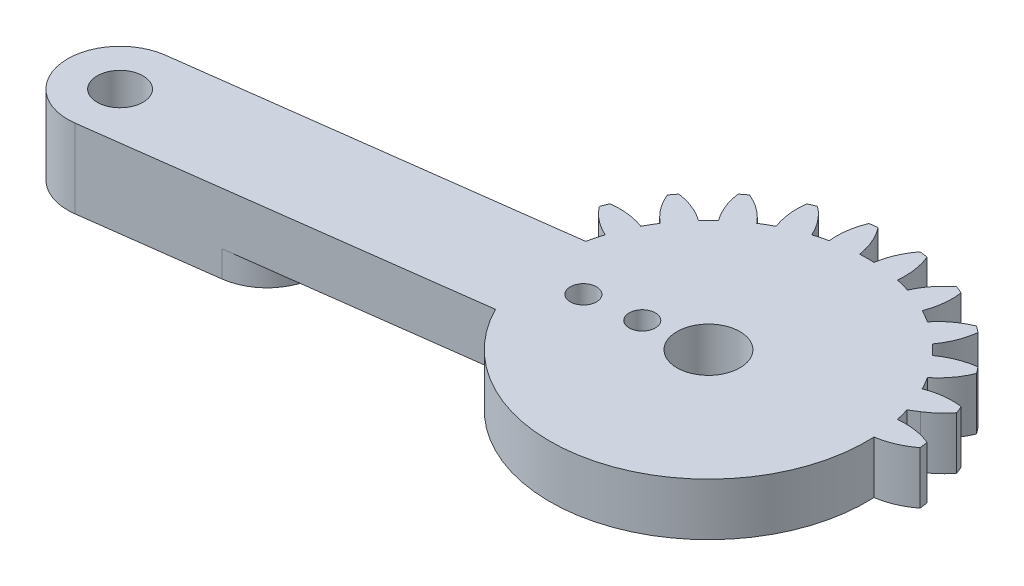
SolidWorks part; units mm, degrees
ref_plane "Front Plane" through (0, 0, 0) normal (0, 0, 1) x (1, 0, 0)
ref_plane "Top Plane" through (0, 0, 0) normal (0, 1, 0) x (1, 0, 0)
ref_plane "Right Plane" through (0, 0, 0) normal (1, 0, 0) x (0, 0, -1)
sketch "Sketch1" plane through (0, 0, 0) normal (0, 1, 0) x (1, 0, 0)
  line L0 (20, 4) -> (2.0816, 4)
  line L1 (2.0816, -4) -> (20, -4)
  arc A0 (2.0816, 4) -> (3.5217, 5.3071) centre (-0.7683, 8.5867) ccw
  arc A1 (3.5217, 5.3071) -> (3.2829, 5.8838) centre (-10.1063, 0) ccw
  arc A2 (3.2829, 5.8838) -> (0.6271, 5.5703) centre (2.5684, 0.5313) ccw
  arc A3 (0.6271, 5.5703) -> (0.0844, 6.5103) centre (-10.1063, 0) ccw
  arc A4 (0.0844, 6.5103) -> (1.6838, 8.6535) centre (-3.3089, 10.711) ccw
  arc A5 (1.6838, 8.6535) -> (1.3038, 9.1487) centre (-10.1063, 0) ccw
  arc A6 (1.3038, 9.1487) -> (-1.1803, 8.1585) centre (1.999, 3.7936) ccw
  arc A7 (-1.1803, 8.1585) -> (-1.9479, 8.926) centre (-10.1063, 0) ccw
  arc A8 (-1.9479, 8.926) -> (-0.9576, 11.4102) centre (-6.3127, 12.1053) ccw
  arc A9 (-0.9576, 11.4102) -> (-1.4528, 11.7901) centre (-10.1063, 0) ccw
  arc A10 (-1.4528, 11.7901) -> (-3.596, 10.1907) centre (0.6046, 6.7975) ccw
  arc A11 (-3.596, 10.1907) -> (-4.5361, 10.7334) centre (-10.1063, 0) ccw
  arc A12 (-4.5361, 10.7334) -> (-4.2225, 13.3892) centre (-9.5751, 12.6747) ccw
  arc A13 (-4.2225, 13.3892) -> (-4.7992, 13.6281) centre (-10.1063, 0) ccw
  arc A14 (-4.7992, 13.6281) -> (-6.4554, 11.5285) centre (-1.5196, 9.3381) ccw
  arc A15 (-6.4554, 11.5285) -> (-7.5039, 11.8094) centre (-10.1063, 0) ccw
  arc A16 (-7.5039, 11.8094) -> (-7.8884, 14.4558) centre (-12.8736, 12.3803) ccw
  arc A17 (-7.8884, 14.4558) -> (-8.5072, 14.5373) centre (-10.1063, 0) ccw
  arc A18 (-8.5072, 14.5373) -> (-9.5636, 12.0806) centre (-4.2291, 11.2423) ccw
  arc A19 (-9.5636, 12.0806) -> (-10.6491, 12.0806) centre (-10.1063, 0) ccw
  arc A20 (-10.6491, 12.0806) -> (-11.7054, 14.5373) centre (-15.9836, 11.2423) ccw
  arc A21 (-11.7054, 14.5373) -> (-12.3243, 14.4558) centre (-10.1063, 0) ccw
  arc A22 (-12.3243, 14.4558) -> (-12.7088, 11.8094) centre (-7.3391, 12.3803) ccw
  arc A23 (-12.7088, 11.8094) -> (-13.7573, 11.5285) centre (-10.1063, 0) ccw
  arc A24 (-13.7573, 11.5285) -> (-15.4135, 13.6281) centre (-18.6931, 9.3381) ccw
  arc A25 (-15.4135, 13.6281) -> (-15.9901, 13.3892) centre (-10.1063, 0) ccw
  arc A26 (-15.9901, 13.3892) -> (-15.6766, 10.7334) centre (-10.6376, 12.6747) ccw
  arc A27 (-15.6766, 10.7334) -> (-16.6166, 10.1907) centre (-10.1063, 0) ccw
  arc A28 (-16.6166, 10.1907) -> (-18.7599, 11.7901) centre (-20.8173, 6.7975) ccw
  arc A29 (-18.7599, 11.7901) -> (-19.255, 11.4102) centre (-10.1063, 0) ccw
  arc A30 (-19.255, 11.4102) -> (-18.2648, 8.926) centre (-13.9, 12.1053) ccw
  arc A31 (-18.2648, 8.926) -> (-19.0324, 8.1585) centre (-10.1063, 0) ccw
  arc A32 (-19.0324, 8.1585) -> (-21.5165, 9.1487) centre (-22.2117, 3.7936) ccw
  arc A33 (-21.5165, 9.1487) -> (-21.8965, 8.6535) centre (-10.1063, 0) ccw
  arc A34 (-21.8965, 8.6535) -> (-20.2971, 6.5103) centre (-16.9038, 10.711) ccw
  arc A35 (-20.2971, 6.5103) -> (-20.8398, 5.5703) centre (-10.1063, 0) ccw
  arc A36 (-20.8398, 5.5703) -> (-23.4956, 5.8838) centre (-22.7811, 0.5313) ccw
  arc A37 (-23.4956, 5.8838) -> (-23.7344, 5.3071) centre (-10.1063, 0) ccw
  arc A38 (-23.7344, 5.3071) -> (-21.6348, 3.6509) centre (-19.4444, 8.5867) ccw
  arc A39 (-21.6348, 3.6509) -> (-21.9157, 2.6025) centre (-10.1063, 0) ccw
  arc A40 (-21.9157, 2.6025) -> (-24.5622, 2.2179) centre (-22.4867, -2.7673) ccw
  arc A41 (-24.5622, 2.2179) -> (-24.6437, 1.5991) centre (-10.1063, 0) ccw
  arc A42 (-24.6437, 1.5991) -> (-22.1869, 0.5427) centre (-21.3486, 5.8773) ccw
  arc A43 (-22.1869, 0.5427) -> (-22.1869, -0.5427) centre (-10.1063, 0) ccw
  arc A44 (-22.1869, -0.5427) -> (-24.6437, -1.5991) centre (-21.3486, -5.8773) ccw
  arc A45 (-24.6437, -1.5991) -> (-24.5622, -2.2179) centre (-10.1063, 0) ccw
  arc A46 (-24.5622, -2.2179) -> (-21.9157, -2.6025) centre (-22.4867, 2.7673) ccw
  arc A47 (-21.9157, -2.6025) -> (-21.6348, -3.6509) centre (-10.1063, 0) ccw
  arc A48 (-21.6348, -3.6509) -> (-23.7344, -5.3071) centre (-19.4444, -8.5867) ccw
  arc A49 (-23.7344, -5.3071) -> (-23.4956, -5.8838) centre (-10.1063, 0) ccw
  arc A50 (-23.4956, -5.8838) -> (-20.8398, -5.5703) centre (-22.7811, -0.5313) ccw
  arc A51 (-20.8398, -5.5703) -> (-20.2971, -6.5103) centre (-10.1063, 0) ccw
  arc A52 (-20.2971, -6.5103) -> (-21.8965, -8.6535) centre (-16.9038, -10.711) ccw
  arc A53 (-21.8965, -8.6535) -> (-21.5165, -9.1487) centre (-10.1063, 0) ccw
  arc A54 (-21.5165, -9.1487) -> (-19.0324, -8.1585) centre (-22.2117, -3.7936) ccw
  arc A55 (-19.0324, -8.1585) -> (-18.2648, -8.926) centre (-10.1063, 0) ccw
  arc A56 (-18.2648, -8.926) -> (-19.255, -11.4102) centre (-13.9, -12.1053) ccw
  arc A57 (-19.255, -11.4102) -> (-18.7599, -11.7901) centre (-10.1063, 0) ccw
  arc A58 (-18.7599, -11.7901) -> (-16.6166, -10.1907) centre (-20.8173, -6.7975) ccw
  arc A59 (-16.6166, -10.1907) -> (-15.6766, -10.7334) centre (-10.1063, 0) ccw
  arc A60 (-15.6766, -10.7334) -> (-15.9901, -13.3892) centre (-10.6376, -12.6747) ccw
  arc A61 (-15.9901, -13.3892) -> (-15.4135, -13.6281) centre (-10.1063, 0) ccw
  arc A62 (-15.4135, -13.6281) -> (-13.7573, -11.5285) centre (-18.6931, -9.3381) ccw
  arc A63 (-13.7573, -11.5285) -> (-12.7088, -11.8094) centre (-10.1063, 0) ccw
  arc A64 (-12.7088, -11.8094) -> (-12.3243, -14.4558) centre (-7.3391, -12.3803) ccw
  arc A65 (-12.3243, -14.4558) -> (-11.7054, -14.5373) centre (-10.1063, 0) ccw
  arc A66 (-11.7054, -14.5373) -> (-10.6491, -12.0806) centre (-15.9836, -11.2423) ccw
  arc A67 (-10.6491, -12.0806) -> (-9.5636, -12.0806) centre (-10.1063, 0) ccw
  arc A68 (-9.5636, -12.0806) -> (-8.5072, -14.5373) centre (-4.2291, -11.2423) ccw
  arc A69 (-8.5072, -14.5373) -> (-7.8884, -14.4558) centre (-10.1063, 0) ccw
  arc A70 (-7.8884, -14.4558) -> (-7.5039, -11.8094) centre (-12.8736, -12.3803) ccw
  arc A71 (-7.5039, -11.8094) -> (-6.4554, -11.5285) centre (-10.1063, 0) ccw
  arc A72 (-6.4554, -11.5285) -> (-4.7992, -13.6281) centre (-1.5196, -9.3381) ccw
  arc A73 (-4.7992, -13.6281) -> (-4.2225, -13.3892) centre (-10.1063, 0) ccw
  arc A74 (-4.2225, -13.3892) -> (-4.5361, -10.7334) centre (-9.5751, -12.6747) ccw
  arc A75 (-4.5361, -10.7334) -> (-3.596, -10.1907) centre (-10.1063, 0) ccw
  arc A76 (-3.596, -10.1907) -> (-1.4528, -11.7901) centre (0.6046, -6.7975) ccw
  arc A77 (-1.4528, -11.7901) -> (-0.9576, -11.4102) centre (-10.1063, 0) ccw
  arc A78 (-0.9576, -11.4102) -> (-1.9479, -8.926) centre (-6.3127, -12.1053) ccw
  arc A79 (-1.9479, -8.926) -> (-1.1803, -8.1585) centre (-10.1063, 0) ccw
  arc A80 (-1.1803, -8.1585) -> (1.3038, -9.1487) centre (1.999, -3.7936) ccw
  arc A81 (1.3038, -9.1487) -> (1.6838, -8.6535) centre (-10.1063, 0) ccw
  arc A82 (1.6838, -8.6535) -> (0.0844, -6.5103) centre (-3.3089, -10.711) ccw
  arc A83 (0.0844, -6.5103) -> (0.6271, -5.5703) centre (-10.1063, 0) ccw
  arc A84 (0.6271, -5.5703) -> (3.2829, -5.8838) centre (2.5684, -0.5313) ccw
  arc A85 (3.2829, -5.8838) -> (3.5217, -5.3071) centre (-10.1063, 0) ccw
  arc A86 (3.5217, -5.3071) -> (2.0816, -4) centre (-0.7683, -8.5867) ccw
  arc A87 (20, -4) -> (20, 4) centre (20, 0) ccw
  circle A88 centre (-10.1063, 0) radius 1.5
  circle A89 centre (20, 0) radius 1.5
  dimension "D1" = 3
  dimension "D2" = 3
  dimension "D4" = 4
  dimension "D3" = 20
extrude "Boss-Extrude1" add sketch "Sketch1" along normal blind 4
sketch "Sketch3" plane through (0, 4, 0) normal (0, 1, 0) x (1, 0, 0)
  line L0 (-10.1063, 0) -> (-40.8563, 0) construction
  line L1 (-10.1063, 0) -> (-49.7641, -5.221)
  line L2 (-10.6284, 3.9658) -> (-50.2862, -1.2553)
  line L3 (-9.5842, -3.9658) -> (-49.242, -9.1868)
  line L4 (-10.1063, 0) -> (-4.5096, 13.5117) construction
  line L5 (-10.1063, 0) -> (-8.1974, 14.4999) construction
  circle A0 centre (-10.1063, 0) radius 1.5
  circle A1 centre (20, 0) radius 1.5 construction
  circle A2 centre (20, 0) radius 1.5
  circle A3 centre (-49.7641, -5.221) radius 1.75
  circle A4 centre (-49.7641, -5.221) radius 4
  circle A5 centre (-10.1063, 0) radius 4
  arc A6 (-4.2225, 13.3892) -> (-4.7992, 13.6281) centre (-10.1063, 0) ccw construction
  arc A7 (-7.8884, 14.4558) -> (-8.5072, 14.5373) centre (-10.1063, 0) ccw construction
  dimension "D2" = 3
  dimension "D5" = 3.5
  dimension "D6" = 8
  dimension "D7" = 8
  dimension "D1" = 40
  dimension "D4" = 7.5
extrude "Boss-Extrude2" add sketch "Sketch3" against normal blind 4
sketch "Sketch4" plane through (0, 4, 0) normal (0, 1, 0) x (1, 0, 0)
  line L0 (20, 4) -> (2.0816, 4) construction
  line L1 (2.0816, -4) -> (20, -4) construction
  line L2 (20, 4) -> (2.0816, 4)
  line L3 (2.0816, -4) -> (20, -4)
  line L4 (2.0816, 4) -> (1.4381, 3.6001)
  line L5 (-21.6245, -5.5509) -> (-20.8986, -5.4553)
  line L6 (-10.1063, 0) -> (0.0844, 6.5103) construction
  line L7 (-10.1063, 0) -> (1.9742, 0.5427) construction
  line L8 (-24.5755, 2.1296) -> (-50.2862, -1.2553)
  line L9 (-49.242, -9.1868) -> (-23.5312, -5.8019)
  line L10 (2.0816, -4) -> (20, -4)
  line L11 (20, 4) -> (2.0816, 4)
  line L12 (-21.9429, 2.4762) -> (-50.2862, -1.2553)
  line L13 (-49.242, -9.1868) -> (-21.6245, -5.5509)
  line L14 (2.0816, -4) -> (20, -4)
  line L15 (20, 4) -> (2.0816, 4)
  circle A0 centre (-10.1063, 0) radius 12.0927
  arc A1 (3.2829, 5.8838) -> (0.6271, 5.5703) centre (2.5684, 0.5313) ccw construction
  arc A2 (3.5217, 5.3071) -> (3.2829, 5.8838) centre (-10.1063, 0) ccw construction
  arc A3 (2.0816, 4) -> (3.5217, 5.3071) centre (-0.7683, 8.5867) ccw construction
  arc A4 (20, -4) -> (20, 4) centre (20, 0) ccw construction
  arc A5 (3.5217, -5.3071) -> (2.0816, -4) centre (-0.7683, -8.5867) ccw construction
  arc A6 (3.2829, -5.8838) -> (3.5217, -5.3071) centre (-10.1063, 0) ccw construction
  arc A7 (0.6271, -5.5703) -> (3.2829, -5.8838) centre (2.5684, -0.5313) ccw construction
  arc A8 (3.2829, 5.8838) -> (0.6271, 5.5703) centre (2.5684, 0.5313) ccw
  arc A9 (3.5217, 5.3071) -> (3.2829, 5.8838) centre (-10.1063, 0) ccw
  arc A10 (2.0816, 4) -> (3.5217, 5.3071) centre (-0.7683, 8.5867) ccw
  arc A11 (20, -4) -> (20, 4) centre (20, 0) ccw
  arc A12 (3.5217, -5.3071) -> (2.0816, -4) centre (-0.7683, -8.5867) ccw
  arc A13 (3.2829, -5.8838) -> (3.5217, -5.3071) centre (-10.1063, 0) ccw
  arc A14 (0.6271, -5.5703) -> (3.2829, -5.8838) centre (2.5684, -0.5313) ccw
  arc A15 (1.9742, 0.5427) -> (4.431, 1.5991) centre (1.1359, 5.8773) ccw
  arc A16 (4.3495, 2.2179) -> (1.7031, 2.6025) centre (2.274, -2.7673) ccw
  arc A17 (4.431, 1.5991) -> (4.3495, 2.2179) centre (-10.1063, 0) ccw
  arc A95 (-21.6348, 3.6509) -> (-21.9157, 2.6025) centre (-10.1063, 0) ccw
  arc A96 (-50.2862, -1.2553) -> (-49.242, -9.1868) centre (-49.7641, -5.221) ccw
  arc A97 (-20.2971, -6.5103) -> (-21.8965, -8.6535) centre (-16.9038, -10.711) ccw
  arc A98 (-21.8965, -8.6535) -> (-21.5165, -9.1487) centre (-10.1063, 0) ccw
  arc A99 (-21.5165, -9.1487) -> (-19.0324, -8.1585) centre (-22.2117, -3.7936) ccw
  arc A100 (-19.0324, -8.1585) -> (-18.2648, -8.926) centre (-10.1063, 0) ccw
  arc A101 (-18.2648, -8.926) -> (-19.255, -11.4102) centre (-13.9, -12.1053) ccw
  arc A102 (-19.255, -11.4102) -> (-18.7599, -11.7901) centre (-10.1063, 0) ccw
  arc A103 (-18.7599, -11.7901) -> (-16.6166, -10.1907) centre (-20.8173, -6.7975) ccw
  arc A104 (-16.6166, -10.1907) -> (-15.6766, -10.7334) centre (-10.1063, 0) ccw
  arc A105 (-15.6766, -10.7334) -> (-15.9901, -13.3892) centre (-10.6376, -12.6747) ccw
  arc A106 (-15.9901, -13.3892) -> (-15.4135, -13.6281) centre (-10.1063, 0) ccw
  arc A107 (-15.4135, -13.6281) -> (-13.7573, -11.5285) centre (-18.6931, -9.3381) ccw
  arc A108 (-13.7573, -11.5285) -> (-12.7088, -11.8094) centre (-10.1063, 0) ccw
  arc A109 (-12.7088, -11.8094) -> (-12.3243, -14.4558) centre (-7.3391, -12.3803) ccw
  arc A110 (-12.3243, -14.4558) -> (-11.7054, -14.5373) centre (-10.1063, 0) ccw
  arc A111 (-11.7054, -14.5373) -> (-10.6491, -12.0806) centre (-15.9836, -11.2423) ccw
  arc A112 (-10.6491, -12.0806) -> (-9.5636, -12.0806) centre (-10.1063, 0) ccw
  arc A113 (-9.5636, -12.0806) -> (-8.5072, -14.5373) centre (-4.2291, -11.2423) ccw
  arc A114 (-8.5072, -14.5373) -> (-7.8884, -14.4558) centre (-10.1063, 0) ccw
  arc A115 (-7.8884, -14.4558) -> (-7.5039, -11.8094) centre (-12.8736, -12.3803) ccw
  arc A116 (-7.5039, -11.8094) -> (-6.4554, -11.5285) centre (-10.1063, 0) ccw
  arc A117 (-6.4554, -11.5285) -> (-4.7992, -13.6281) centre (-1.5196, -9.3381) ccw
  arc A118 (-4.7992, -13.6281) -> (-4.2225, -13.3892) centre (-10.1063, 0) ccw
  arc A119 (-4.2225, -13.3892) -> (-4.5361, -10.7334) centre (-9.5751, -12.6747) ccw
  arc A120 (-4.5361, -10.7334) -> (-3.596, -10.1907) centre (-10.1063, 0) ccw
  arc A121 (-3.596, -10.1907) -> (-1.4528, -11.7901) centre (0.6046, -6.7975) ccw
  arc A122 (-1.4528, -11.7901) -> (-0.9576, -11.4102) centre (-10.1063, 0) ccw
  arc A123 (-0.9576, -11.4102) -> (-1.9479, -8.926) centre (-6.3127, -12.1053) ccw
  arc A124 (-1.9479, -8.926) -> (-1.1803, -8.1585) centre (-10.1063, 0) ccw
  arc A125 (-1.1803, -8.1585) -> (1.3038, -9.1487) centre (1.999, -3.7936) ccw
  arc A126 (1.3038, -9.1487) -> (1.6838, -8.6535) centre (-10.1063, 0) ccw
  arc A127 (1.6838, -8.6535) -> (0.0844, -6.5103) centre (-3.3089, -10.711) ccw
  arc A128 (0.0844, -6.5103) -> (0.6271, -5.5703) centre (-10.1063, 0) ccw
  arc A129 (0.6271, -5.5703) -> (3.2829, -5.8838) centre (2.5684, -0.5313) ccw
  arc A130 (3.2829, -5.8838) -> (3.5217, -5.3071) centre (-10.1063, 0) ccw
  arc A131 (3.5217, -5.3071) -> (2.0816, -4) centre (-0.7683, -8.5867) ccw
  arc A132 (20, -4) -> (20, 4) centre (20, 0) ccw
  arc A133 (2.0816, 4) -> (3.5217, 5.3071) centre (-0.7683, 8.5867) ccw
  arc A134 (3.5217, 5.3071) -> (3.2829, 5.8838) centre (-10.1063, 0) ccw
  arc A135 (3.2829, 5.8838) -> (0.6271, 5.5703) centre (2.5684, 0.5313) ccw
  arc A136 (0.6271, 5.5703) -> (0.0844, 6.5103) centre (-10.1063, 0) ccw
  arc A137 (0.0844, 6.5103) -> (1.6838, 8.6535) centre (-3.3089, 10.711) ccw
  arc A138 (1.6838, 8.6535) -> (1.3038, 9.1487) centre (-10.1063, 0) ccw
  arc A139 (1.3038, 9.1487) -> (-1.1803, 8.1585) centre (1.999, 3.7936) ccw
  arc A140 (-1.1803, 8.1585) -> (-1.9479, 8.926) centre (-10.1063, 0) ccw
  arc A141 (-1.9479, 8.926) -> (-0.9576, 11.4102) centre (-6.3127, 12.1053) ccw
  arc A142 (-0.9576, 11.4102) -> (-1.4528, 11.7901) centre (-10.1063, 0) ccw
  arc A143 (-1.4528, 11.7901) -> (-3.596, 10.1907) centre (0.6046, 6.7975) ccw
  arc A144 (-3.596, 10.1907) -> (-4.5361, 10.7334) centre (-10.1063, 0) ccw
  arc A145 (-4.5361, 10.7334) -> (-4.2225, 13.3892) centre (-9.5751, 12.6747) ccw
  arc A146 (-4.2225, 13.3892) -> (-4.7992, 13.6281) centre (-10.1063, 0) ccw
  arc A147 (-4.7992, 13.6281) -> (-6.4554, 11.5285) centre (-1.5196, 9.3381) ccw
  arc A148 (-6.4554, 11.5285) -> (-7.5039, 11.8094) centre (-10.1063, 0) ccw
  arc A149 (-7.5039, 11.8094) -> (-7.8884, 14.4558) centre (-12.8736, 12.3803) ccw
  arc A150 (-7.8884, 14.4558) -> (-8.5072, 14.5373) centre (-10.1063, 0) ccw
  arc A151 (-8.5072, 14.5373) -> (-9.5636, 12.0806) centre (-4.2291, 11.2423) ccw
  arc A152 (-9.5636, 12.0806) -> (-10.6491, 12.0806) centre (-10.1063, 0) ccw
  arc A153 (-10.6491, 12.0806) -> (-11.7054, 14.5373) centre (-15.9836, 11.2423) ccw
  arc A154 (-11.7054, 14.5373) -> (-12.3243, 14.4558) centre (-10.1063, 0) ccw
  arc A155 (-12.3243, 14.4558) -> (-12.7088, 11.8094) centre (-7.3391, 12.3803) ccw
  arc A156 (-12.7088, 11.8094) -> (-13.7573, 11.5285) centre (-10.1063, 0) ccw
  arc A157 (-13.7573, 11.5285) -> (-15.4135, 13.6281) centre (-18.6931, 9.3381) ccw
  arc A158 (-15.4135, 13.6281) -> (-15.9901, 13.3892) centre (-10.1063, 0) ccw
  arc A159 (-15.9901, 13.3892) -> (-15.6766, 10.7334) centre (-10.6376, 12.6747) ccw
  arc A160 (-15.6766, 10.7334) -> (-16.6166, 10.1907) centre (-10.1063, 0) ccw
  arc A161 (-16.6166, 10.1907) -> (-18.7599, 11.7901) centre (-20.8173, 6.7975) ccw
  arc A162 (-18.7599, 11.7901) -> (-19.255, 11.4102) centre (-10.1063, 0) ccw
  arc A163 (-19.255, 11.4102) -> (-18.2648, 8.926) centre (-13.9, 12.1053) ccw
  arc A164 (-18.2648, 8.926) -> (-19.0324, 8.1585) centre (-10.1063, 0) ccw
  arc A165 (-19.0324, 8.1585) -> (-21.5165, 9.1487) centre (-22.2117, 3.7936) ccw
  arc A166 (-21.5165, 9.1487) -> (-21.8965, 8.6535) centre (-10.1063, 0) ccw
  arc A167 (-21.8965, 8.6535) -> (-20.2971, 6.5103) centre (-16.9038, 10.711) ccw
  arc A168 (-20.2971, 6.5103) -> (-20.8398, 5.5703) centre (-10.1063, 0) ccw
  arc A169 (-20.8398, 5.5703) -> (-23.4956, 5.8838) centre (-22.7811, 0.5313) ccw
  arc A170 (-23.4956, 5.8838) -> (-23.7344, 5.3071) centre (-10.1063, 0) ccw
  arc A171 (-23.7344, 5.3071) -> (-21.6348, 3.6509) centre (-19.4444, 8.5867) ccw
  arc A172 (-21.6348, 3.6509) -> (-21.9157, 2.6025) centre (-10.1063, 0) ccw
  arc A175 (-23.4956, -5.8838) -> (-20.8398, -5.5703) centre (-22.7811, -0.5313) ccw
  arc A176 (-50.2862, -1.2553) -> (-49.242, -9.1868) centre (-49.7641, -5.221) ccw
  arc A177 (-20.2971, -6.5103) -> (-21.8965, -8.6535) centre (-16.9038, -10.711) ccw
  arc A178 (-21.8965, -8.6535) -> (-21.5165, -9.1487) centre (-10.1063, 0) ccw
  arc A179 (-21.5165, -9.1487) -> (-19.0324, -8.1585) centre (-22.2117, -3.7936) ccw
  arc A180 (-19.0324, -8.1585) -> (-18.2648, -8.926) centre (-10.1063, 0) ccw
  arc A181 (-18.2648, -8.926) -> (-19.255, -11.4102) centre (-13.9, -12.1053) ccw
  arc A182 (-19.255, -11.4102) -> (-18.7599, -11.7901) centre (-10.1063, 0) ccw
  arc A183 (-18.7599, -11.7901) -> (-16.6166, -10.1907) centre (-20.8173, -6.7975) ccw
  arc A184 (-16.6166, -10.1907) -> (-15.6766, -10.7334) centre (-10.1063, 0) ccw
  arc A185 (-15.6766, -10.7334) -> (-15.9901, -13.3892) centre (-10.6376, -12.6747) ccw
  arc A186 (-15.9901, -13.3892) -> (-15.4135, -13.6281) centre (-10.1063, 0) ccw
  arc A187 (-15.4135, -13.6281) -> (-13.7573, -11.5285) centre (-18.6931, -9.3381) ccw
  arc A188 (-13.7573, -11.5285) -> (-12.7088, -11.8094) centre (-10.1063, 0) ccw
  arc A189 (-12.7088, -11.8094) -> (-12.3243, -14.4558) centre (-7.3391, -12.3803) ccw
  arc A190 (-12.3243, -14.4558) -> (-11.7054, -14.5373) centre (-10.1063, 0) ccw
  arc A191 (-11.7054, -14.5373) -> (-10.6491, -12.0806) centre (-15.9836, -11.2423) ccw
  arc A192 (-10.6491, -12.0806) -> (-9.5636, -12.0806) centre (-10.1063, 0) ccw
  arc A193 (-9.5636, -12.0806) -> (-8.5072, -14.5373) centre (-4.2291, -11.2423) ccw
  arc A194 (-8.5072, -14.5373) -> (-7.8884, -14.4558) centre (-10.1063, 0) ccw
  arc A195 (-7.8884, -14.4558) -> (-7.5039, -11.8094) centre (-12.8736, -12.3803) ccw
  arc A196 (-7.5039, -11.8094) -> (-6.4554, -11.5285) centre (-10.1063, 0) ccw
  arc A197 (-6.4554, -11.5285) -> (-4.7992, -13.6281) centre (-1.5196, -9.3381) ccw
  arc A198 (-4.7992, -13.6281) -> (-4.2225, -13.3892) centre (-10.1063, 0) ccw
  arc A199 (-4.2225, -13.3892) -> (-4.5361, -10.7334) centre (-9.5751, -12.6747) ccw
  arc A200 (-4.5361, -10.7334) -> (-3.596, -10.1907) centre (-10.1063, 0) ccw
  arc A201 (-3.596, -10.1907) -> (-1.4528, -11.7901) centre (0.6046, -6.7975) ccw
  arc A202 (-1.4528, -11.7901) -> (-0.9576, -11.4102) centre (-10.1063, 0) ccw
  arc A203 (-0.9576, -11.4102) -> (-1.9479, -8.926) centre (-6.3127, -12.1053) ccw
  arc A204 (-1.9479, -8.926) -> (-1.1803, -8.1585) centre (-10.1063, 0) ccw
  arc A205 (-1.1803, -8.1585) -> (1.3038, -9.1487) centre (1.999, -3.7936) ccw
  arc A206 (1.3038, -9.1487) -> (1.6838, -8.6535) centre (-10.1063, 0) ccw
  arc A207 (1.6838, -8.6535) -> (0.0844, -6.5103) centre (-3.3089, -10.711) ccw
  arc A208 (0.0844, -6.5103) -> (0.6271, -5.5703) centre (-10.1063, 0) ccw
  arc A209 (0.6271, -5.5703) -> (3.2829, -5.8838) centre (2.5684, -0.5313) ccw
  arc A210 (3.2829, -5.8838) -> (3.5217, -5.3071) centre (-10.1063, 0) ccw
  arc A211 (3.5217, -5.3071) -> (2.0816, -4) centre (-0.7683, -8.5867) ccw
  arc A212 (20, -4) -> (20, 4) centre (20, 0) ccw
  arc A213 (2.0816, 4) -> (3.5217, 5.3071) centre (-0.7683, 8.5867) ccw
  arc A214 (3.5217, 5.3071) -> (3.2829, 5.8838) centre (-10.1063, 0) ccw
  arc A215 (3.2829, 5.8838) -> (0.6271, 5.5703) centre (2.5684, 0.5313) ccw
  arc A216 (0.6271, 5.5703) -> (0.0844, 6.5103) centre (-10.1063, 0) ccw
  arc A217 (0.0844, 6.5103) -> (1.6838, 8.6535) centre (-3.3089, 10.711) ccw
  arc A218 (1.6838, 8.6535) -> (1.3038, 9.1487) centre (-10.1063, 0) ccw
  arc A219 (1.3038, 9.1487) -> (-1.1803, 8.1585) centre (1.999, 3.7936) ccw
  arc A220 (-1.1803, 8.1585) -> (-1.9479, 8.926) centre (-10.1063, 0) ccw
  arc A221 (-1.9479, 8.926) -> (-0.9576, 11.4102) centre (-6.3127, 12.1053) ccw
  arc A222 (-0.9576, 11.4102) -> (-1.4528, 11.7901) centre (-10.1063, 0) ccw
  arc A223 (-1.4528, 11.7901) -> (-3.596, 10.1907) centre (0.6046, 6.7975) ccw
  arc A224 (-3.596, 10.1907) -> (-4.5361, 10.7334) centre (-10.1063, 0) ccw
  arc A225 (-4.5361, 10.7334) -> (-4.2225, 13.3892) centre (-9.5751, 12.6747) ccw
  arc A226 (-4.2225, 13.3892) -> (-4.7992, 13.6281) centre (-10.1063, 0) ccw
  arc A227 (-4.7992, 13.6281) -> (-6.4554, 11.5285) centre (-1.5196, 9.3381) ccw
  arc A228 (-6.4554, 11.5285) -> (-7.5039, 11.8094) centre (-10.1063, 0) ccw
  arc A229 (-7.5039, 11.8094) -> (-7.8884, 14.4558) centre (-12.8736, 12.3803) ccw
  arc A230 (-7.8884, 14.4558) -> (-8.5072, 14.5373) centre (-10.1063, 0) ccw
  arc A231 (-8.5072, 14.5373) -> (-9.5636, 12.0806) centre (-4.2291, 11.2423) ccw
  arc A232 (-9.5636, 12.0806) -> (-10.6491, 12.0806) centre (-10.1063, 0) ccw
  arc A233 (-10.6491, 12.0806) -> (-11.7054, 14.5373) centre (-15.9836, 11.2423) ccw
  arc A234 (-11.7054, 14.5373) -> (-12.3243, 14.4558) centre (-10.1063, 0) ccw
  arc A235 (-12.3243, 14.4558) -> (-12.7088, 11.8094) centre (-7.3391, 12.3803) ccw
  arc A236 (-12.7088, 11.8094) -> (-13.7573, 11.5285) centre (-10.1063, 0) ccw
  arc A237 (-13.7573, 11.5285) -> (-15.4135, 13.6281) centre (-18.6931, 9.3381) ccw
  arc A238 (-15.4135, 13.6281) -> (-15.9901, 13.3892) centre (-10.1063, 0) ccw
  arc A239 (-15.9901, 13.3892) -> (-15.6766, 10.7334) centre (-10.6376, 12.6747) ccw
  arc A240 (-15.6766, 10.7334) -> (-16.6166, 10.1907) centre (-10.1063, 0) ccw
  arc A241 (-16.6166, 10.1907) -> (-18.7599, 11.7901) centre (-20.8173, 6.7975) ccw
  arc A242 (-18.7599, 11.7901) -> (-19.255, 11.4102) centre (-10.1063, 0) ccw
  arc A243 (-19.255, 11.4102) -> (-18.2648, 8.926) centre (-13.9, 12.1053) ccw
  arc A244 (-18.2648, 8.926) -> (-19.0324, 8.1585) centre (-10.1063, 0) ccw
  arc A245 (-19.0324, 8.1585) -> (-21.5165, 9.1487) centre (-22.2117, 3.7936) ccw
  arc A246 (-21.5165, 9.1487) -> (-21.8965, 8.6535) centre (-10.1063, 0) ccw
  arc A247 (-21.8965, 8.6535) -> (-20.2971, 6.5103) centre (-16.9038, 10.711) ccw
  arc A248 (-20.2971, 6.5103) -> (-20.8398, 5.5703) centre (-10.1063, 0) ccw
  arc A249 (-20.8398, 5.5703) -> (-23.4956, 5.8838) centre (-22.7811, 0.5313) ccw
  arc A250 (-23.4956, 5.8838) -> (-23.7344, 5.3071) centre (-10.1063, 0) ccw
  arc A251 (-23.7344, 5.3071) -> (-21.6348, 3.6509) centre (-19.4444, 8.5867) ccw
  arc A252 (-23.4956, -5.8838) -> (-20.8398, -5.5703) centre (-22.7811, -0.5313) ccw
  arc A253 (-20.8398, -5.5703) -> (-20.2971, -6.5103) centre (-10.1063, 0) ccw
  arc A254 (-20.8398, -5.5703) -> (-20.2971, -6.5103) centre (-10.1063, 0) ccw
  arc A255 (-23.5312, -5.8019) -> (-23.4956, -5.8838) centre (-10.1063, 0) ccw
  arc A256 (-23.5312, -5.8019) -> (-23.4956, -5.8838) centre (-10.1063, 0) ccw
  arc A257 (-21.9157, 2.6025) -> (-24.5622, 2.2179) centre (-22.4867, -2.7673) ccw
  arc A258 (-21.9157, 2.6025) -> (-24.5622, 2.2179) centre (-22.4867, -2.7673) ccw
  arc A259 (-24.5622, 2.2179) -> (-24.5755, 2.1296) centre (-10.1063, 0) ccw
  arc A260 (-24.5622, 2.2179) -> (-24.5755, 2.1296) centre (-10.1063, 0) ccw
  point P40 (-10.1063, 0)
  dimension "D2" = 24.1855
  dimension "D4" = 30
  dimension "D1" = 0
  dimension "D3" = 2
extrude "Cut-Extrude1" cut sketch "Sketch4" against normal blind 4 contours A178 A179 A0 L5 A177 | A182 A183 A0 A181 | A186 A187 A0 A185 | A190 A191 A0 A189 | A194 A195 A0 A193 | A198 A199 A0 A197 | A202 A203 A0 A201 | A206 A207 A0 A205 | A258 A260 L12 A0 | L13 A256 A252 A0 L5 | A0 A14 A13 A12 L3 A11 L2 L4
sketch "Sketch5" plane through (0, 4, 0) normal (0, 1, 0) x (1, 0, 0)
  line L0 (-10.1063, 0) -> (-49.7641, -5.221) construction
  circle A0 centre (-10.1063, 0) radius 2.4
  circle A2 centre (-14.5678, -0.5874) radius 1
  circle A4 centre (-18.5336, -1.1095) radius 1
  dimension "D1" = 4.8
  dimension "D2" = 4.5
  dimension "D3" = 2
  dimension "D4" = 2
  dimension "D5" = 4
extrude "Cut-Extrude2" cut sketch "Sketch5" against normal up to next
sketch "Sketch7" plane through (0, 4, 0) normal (0, 1, 0) x (1, 0, 0)
  circle A0 centre (-10.1063, 0) radius 13.45 construction
  circle A1 centre (-10.1063, 0) radius 13.45
sketch "Sketch8" plane through (0, 0, 0) normal (0, -1, 0) x (1, 0, 0)
  line L0 (-39.8497, 3.9158) -> (-49.7641, 5.221) construction
  line L1 (-20.8986, 5.4553) -> (-49.242, 9.1868) construction
  line L2 (-39.3276, 7.8816) -> (-49.242, 9.1868)
  line L3 (-21.9429, -2.4762) -> (-50.2862, 1.2553) construction
  line L4 (-40.3718, -0.05) -> (-50.2862, 1.2553)
  arc A0 (-40.3718, -0.05) -> (-39.3276, 7.8816) centre (-39.8497, 3.9158) ccw
  arc A1 (-49.242, 9.1868) -> (-50.2862, 1.2553) centre (-49.7641, 5.221) ccw construction
  arc A2 (-49.242, 9.1868) -> (-50.2862, 1.2553) centre (-49.7641, 5.221) ccw
  circle A3 centre (-49.7641, 5.221) radius 1.75 construction
  circle A4 centre (-49.7641, 5.221) radius 1.75
  dimension "D1" = 10
extrude "Boss-Extrude3" add sketch "Sketch8" along normal blind 2
